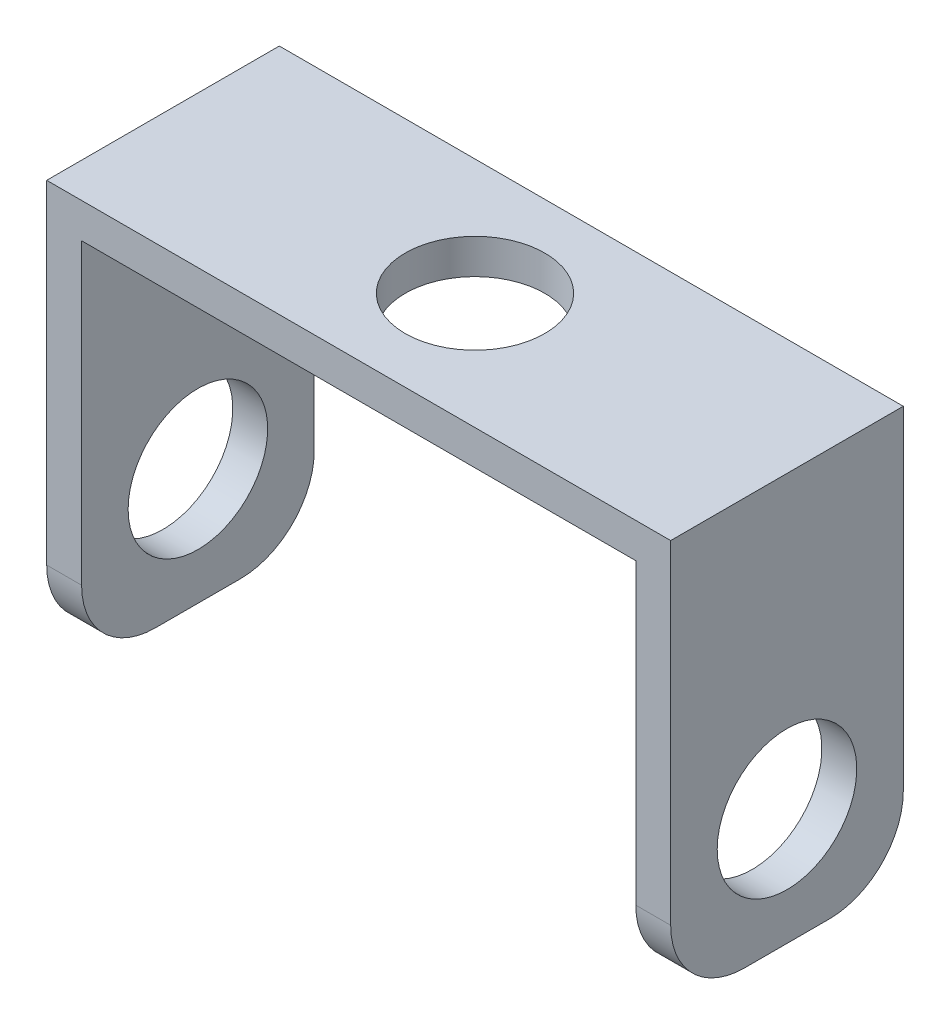
SolidWorks part; units mm, degrees
ref_plane "Front Plane" through (0, 0, 0) normal (0, 0, 1) x (1, 0, 0)
ref_plane "Top Plane" through (0, 0, 0) normal (0, 1, 0) x (1, 0, 0)
ref_plane "Right Plane" through (0, 0, 0) normal (1, 0, 0) x (0, 0, -1)
sketch "Sketch2" plane through (0, 0, 0) normal (0, 1, 0) x (1, 0, 0)
  line L0 (23.825, 0) -> (23.825, -20) construction
  line L1 (0, 0) -> (47.65, 0)
  line L2 (0, 0) -> (0, -20)
  line L3 (0, -20) -> (47.65, -20)
  line L4 (47.65, 0) -> (47.65, -20)
  circle A0 centre (23.825, -10) radius 6
  dimension "D3" = 12
  dimension "D1" = 47.65
  dimension "D2" = 20
extrude "Boss-Extrude1" add sketch "Sketch2" along normal blind 3
sketch "Sketch3" plane through (47.65, 0, 0) normal (1, 0, 0) x (0, 0, -1)
  line L1 (-20, 3) -> (0, 3)
  line L2 (-20, 3) -> (-20, -32)
  line L3 (-20, -32) -> (0, -32)
  line L4 (0, 3) -> (0, -32)
  dimension "D1" = 35
extrude "Boss-Extrude3" add sketch "Sketch3" along normal blind 3
sketch "Sketch4" plane through (0, 0, 0) normal (-1, 0, 0) x (0, 0, 1)
  line L1 (0, 3) -> (20, 3)
  line L2 (0, 3) -> (0, -32)
  line L3 (0, -32) -> (20, -32)
  line L4 (20, 3) -> (20, -32)
  dimension "D1" = 35
  dimension "D2" = 20
extrude "Boss-Extrude4" add sketch "Sketch4" along normal blind 3
sketch "Sketch5" plane through (-3, 0, 0) normal (-1, 0, 0) x (0, 0, 1)
  line L0 (10, 3) -> (10, -32) construction
  line L1 (20, 3) -> (0, 3) construction
  line L2 (0, -32) -> (20, -32) construction
  circle A0 centre (10, -22) radius 6
  dimension "D1" = 25
  dimension "D3" = 12
extrude "Cut-Extrude1" cut sketch "Sketch5" against normal up to surface (53.65 mm away) up to face at (50.65, -14.5, 10)
fillet "Fillet1" radius 6.35 4 edges at (-1.5, -32, 0) (-1.5, -32, 20) (49.15, -32, 0) (49.15, -32, 20)
